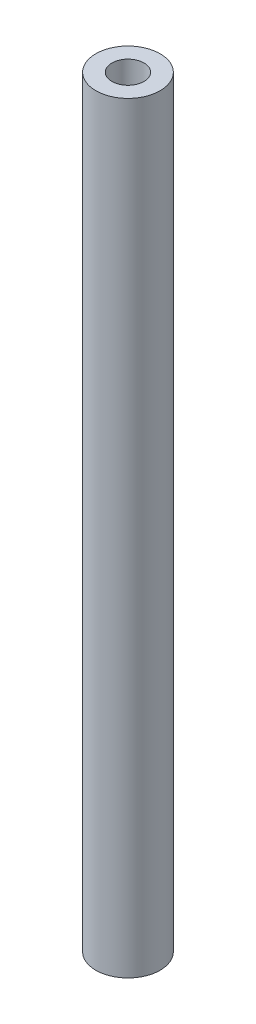
SolidWorks part; units mm, degrees
ref_plane "Alzado" through (0, 0, 0) normal (0, 0, 1) x (1, 0, 0)
ref_plane "Planta" through (0, 0, 0) normal (0, 1, 0) x (1, 0, 0)
ref_plane "Vista lateral" through (0, 0, 0) normal (1, 0, 0) x (0, 0, -1)
sketch "Croquis1" plane through (0, 0, 0) normal (0, 1, 0) x (1, 0, 0)
  circle A0 centre (0, 0) radius 4.7625
  dimension "D1" = 9.525
extrude "Saliente-Extruir1" add sketch "Croquis1" along normal blind 113
sketch "Croquis2" plane through (0, 113, 0) normal (0, 1, 0) x (1, 0, 0)
  circle A0 centre (0, 0) radius 2.3813
  dimension "D1" = 4.7625
extrude "Cortar-Extruir1" cut sketch "Croquis2" against normal blind 10
ref_plane "Plano1" through (0, 56.5, 0) normal (0, 1, 0) x (1, 0, 0)
mirror "Simetría1" about plane through (0, 56.5, 0) normal (0, 1, 0) of "Cortar-Extruir1"
